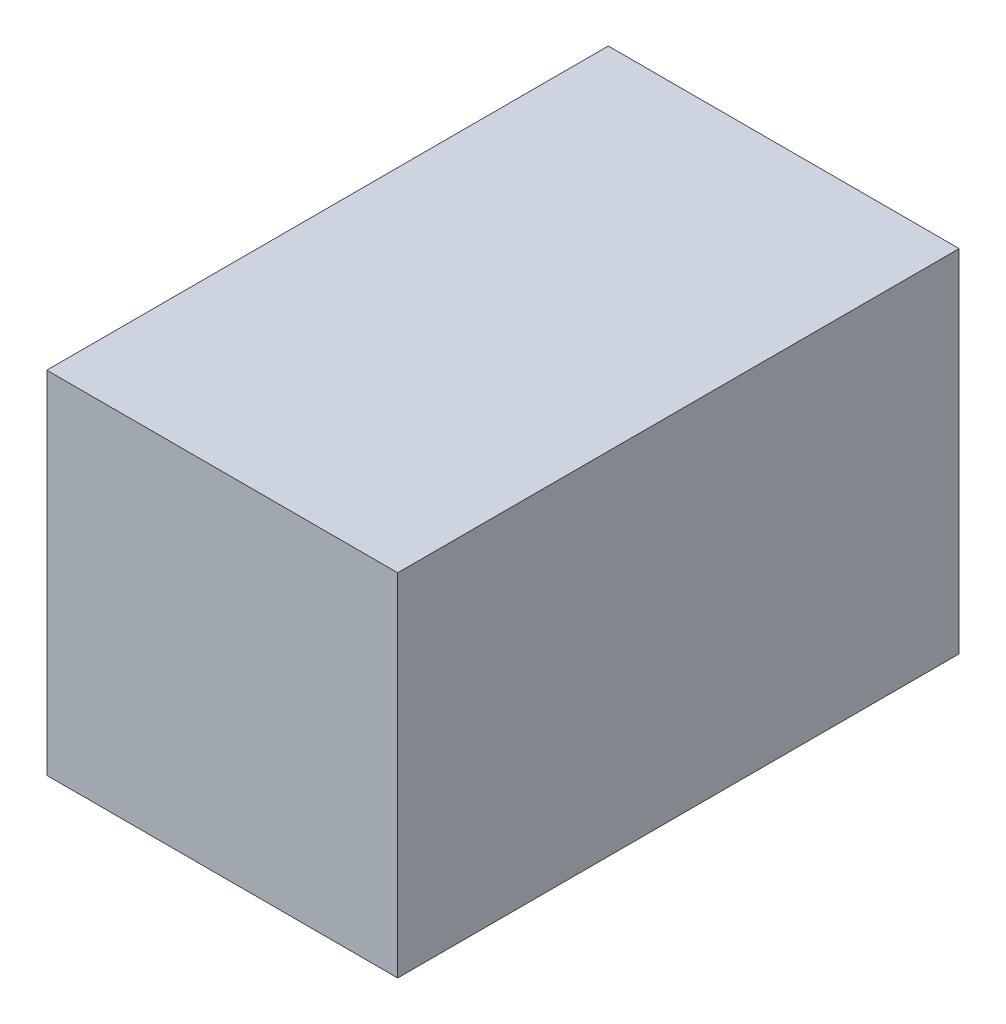
SolidWorks part; units mm, degrees
ref_plane "Front Plane" through (0, 0, 0) normal (0, 0, 1) x (1, 0, 0)
ref_plane "Top Plane" through (0, 0, 0) normal (0, 1, 0) x (1, 0, 0)
ref_plane "Right Plane" through (0, 0, 0) normal (1, 0, 0) x (0, 0, -1)
sketch "Sketch1" plane through (0, 0, 0) normal (0, 0, 1) x (1, 0, 0)
  line L1 (127, -127) -> (-127, -127)
  line L2 (127, -127) -> (127, 127)
  line L3 (127, 127) -> (-127, 127)
  line L4 (-127, -127) -> (-127, 127)
  line L5 (127, -127) -> (-127, 127) construction
  line L6 (127, 127) -> (-127, -127) construction
  point P0 (0, 0)
  dimension "D1" = 254
  dimension "D2" = 254
extrude "Boss-Extrude1" add sketch "Sketch1" along normal blind 406.4
